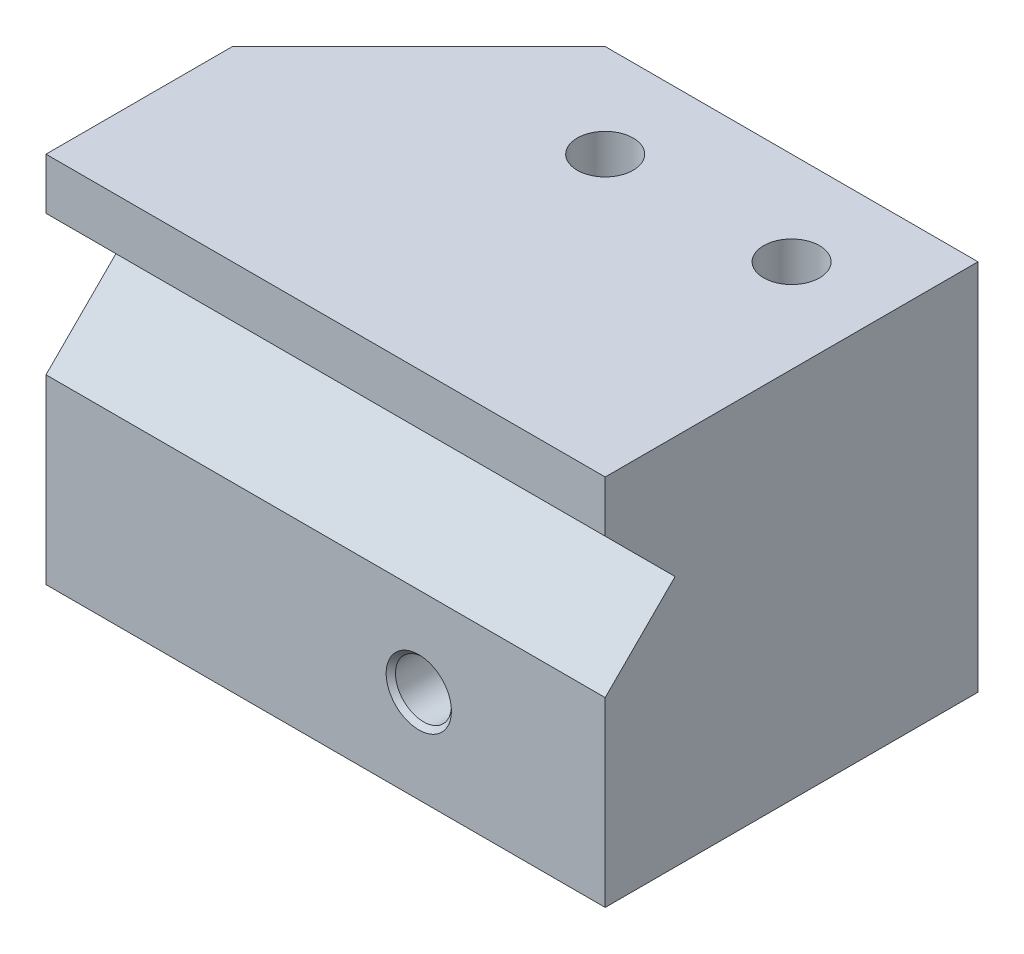
SolidWorks part; units mm, degrees
ref_plane "Plan de face" through (0, 0, 0) normal (0, 0, 1) x (1, 0, 0)
ref_plane "Plan de dessus" through (0, 0, 0) normal (0, 1, 0) x (1, 0, 0)
ref_plane "Plan de droite" through (0, 0, 0) normal (1, 0, 0) x (0, 0, -1)
sketch "Esquisse1" plane through (0, 0, 0) normal (0, 0, 1) x (1, 0, 0)
  line L1 (-15, -10) -> (15, -10)
  line L2 (-15, -10) -> (-15, 10)
  line L3 (-15, 10) -> (15, 10)
  line L4 (15, -10) -> (15, 10)
  line L5 (-15, -10) -> (15, 10) construction
  line L6 (-15, 10) -> (15, -10) construction
  point P1 (0, 0)
  dimension "D1" = 30
  dimension "D2" = 20
extrude "Extrusion1" add sketch "Esquisse1" along normal blind 20
sketch "Esquisse2" plane through (-15, 0, 0) normal (-1, 0, 0) x (0, 0, 1)
  line L0 (20, 7.25) -> (16.25, 3.5)
  line L1 (20, 10) -> (20, -10) construction
  line L2 (16.25, 3.5) -> (20, -0.25)
  line L3 (20, -10) -> (0, -10) construction
  dimension "D1" = 7.5
  dimension "D2" = 13.5
extrude "Extrusion2" cut sketch "Esquisse2" against normal through all and the other way through all
sketch "Esquisse3" plane through (0, 10, 0) normal (0, 1, 0) x (1, 0, 0)
  line L0 (15, -20) -> (15, 0) construction
  line L1 (15, 0) -> (-15, 0) construction
  circle A0 centre (10, -5) radius 1.5
  circle A1 centre (0, -5) radius 1.5
  dimension "D3" = 3
  dimension "D5" = 3
  dimension "D1" = 5
  dimension "D2" = 10
  dimension "D4" = 5
extrude "Extrusion3" cut sketch "Esquisse3" against normal through all
chamfer "Chanfrein1" distance 10 angle 45 1 edges at (-15, 0, 0)
hole_wizard "Trou taraudé M31" positions "Esquisse3D1" profile "Esquisse4" tap size "M3" standard "ISO" end condition through all
sketch3d "Esquisse3D1"
  line L0 (-15, -10, 20) -> (15, -10, 20) construction
  line L1 (15, -10, 20) -> (15, -0.25, 20) construction
  point P0 (5, -5, 20)
  dimension "D1" = 5
  dimension "D2" = 10
sketch "Esquisse4" plane through (5, -5, 20) normal (1, 0, 0) x (0, -1, 0)
  line L0 (0, 0) -> (0, 20)
  line L1 (0, 20) -> (1.75, 20)
  line L2 (1.5, 19.75) -> (1.5, 0.25)
  line L3 (1.5, 0.25) -> (1.75, 0)
  line L5 (1.75, 0) -> (0, 0)
  line L6 (-1.5, 0.25) -> (-1.75, 0) construction
  line L7 (1.75, 20) -> (1.5, 19.75)
  line L8 (-1.75, 20) -> (-1.5, 19.75) construction
  line L11 (0, -6.35) -> (0, 107.95) construction
  dimension "Diamètre principal du filetage" = 3
  dimension "Profondeur du trou pour taraudage jusqu'au prochain" = 20
  dimension "Diamètre du fraisage entrant" = 3.5
  dimension "Angle du fraisage entrant" = 90
  dimension "Diamètre du fraisage débouchant" = 3.5
  dimension "Angle du fraisage débouchant" = 90
